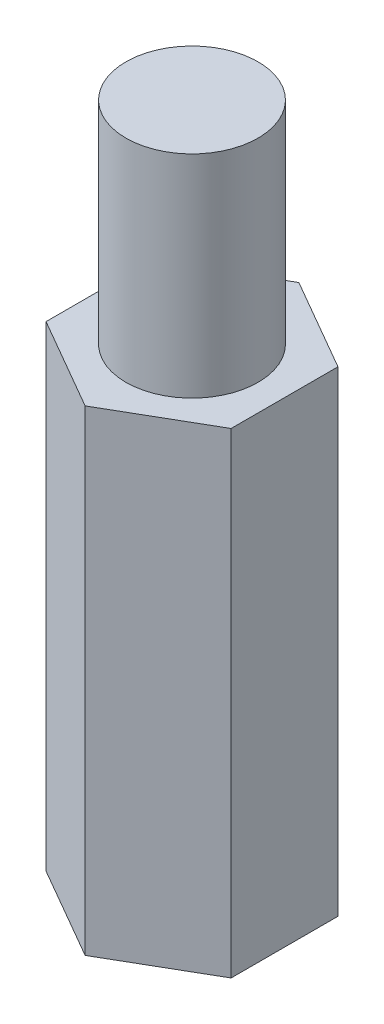
SolidWorks part; units mm, degrees
ref_plane "前视基准面" through (0, 0, 0) normal (0, 0, 1) x (1, 0, 0)
ref_plane "上视基准面" through (0, 0, 0) normal (0, 1, 0) x (1, 0, 0)
ref_plane "右视基准面" through (0, 0, 0) normal (1, 0, 0) x (0, 0, -1)
sketch "草图2" plane through (0, 0, 0) normal (0, 1, 0) x (1, 0, 0)
  line L1 (0, -4.0415) -> (3.5, -2.0207)
  line L2 (3.5, -2.0207) -> (3.5, 2.0207)
  line L3 (3.5, 2.0207) -> (0, 4.0415)
  line L4 (0, 4.0415) -> (-3.5, 2.0207)
  line L5 (-3.5, 2.0207) -> (-3.5, -2.0207)
  line L6 (-3.5, -2.0207) -> (0, -4.0415)
  circle A0 centre (0, 0) radius 3.5 construction
  dimension "D1" = 7
extrude "凸台-拉伸1" add sketch "草图2" along normal blind 30 and the other way blind 0.0001
sketch "草图3" plane through (0, -0.0001, 0) normal (0, -1, 0) x (1, 0, 0)
  circle A0 centre (0, 0) radius 2.5
extrude "切除-拉伸1" cut sketch "草图3" against normal blind 20
sketch "草图4" plane through (0, 30, 0) normal (0, 1, 0) x (1, 0, 0)
  circle A0 centre (0, 0) radius 2.5
extrude "凸台-拉伸2" add sketch "草图4" along normal blind 8
sketch "草图5" plane through (0, -0.0001, 0) normal (0, -1, 0) x (1, 0, 0)
  circle A0 centre (0, 0) radius 7.9007
extrude "切除-拉伸2" cut sketch "草图5" against normal blind 2
sketch "草图6" plane through (0, 1.9999, 0) normal (0, -1, 0) x (1, 0, 0)
  circle A0 centre (-3.086, 4.4653) radius 13.9707
extrude "切除-拉伸3" cut sketch "草图6" against normal blind 10
